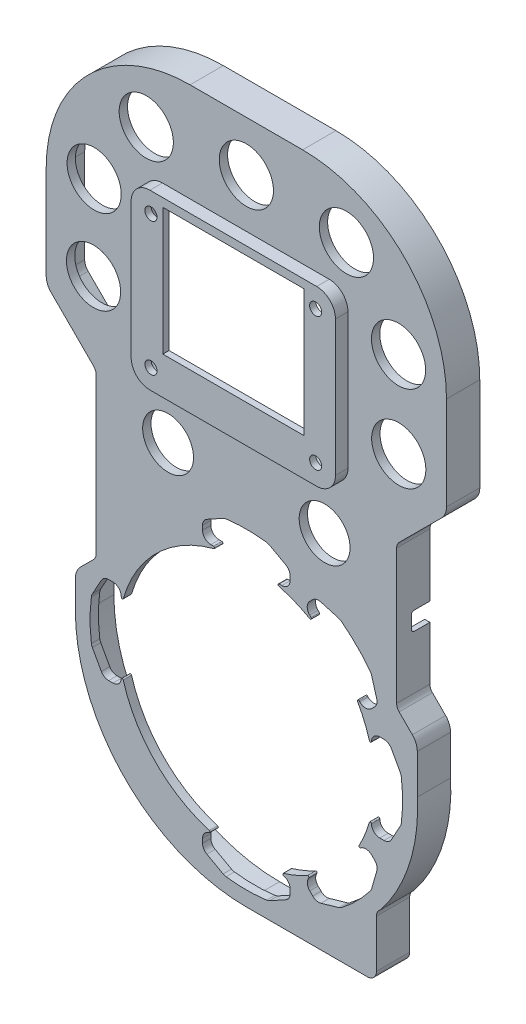
SolidWorks part; units mm, degrees
ref_plane "Front Plane" through (0, 0, 0) normal (0, 0, 1) x (1, 0, 0)
ref_plane "Top Plane" through (0, 0, 0) normal (0, 1, 0) x (1, 0, 0)
ref_plane "Right Plane" through (0, 0, 0) normal (1, 0, 0) x (0, 0, -1)
sketch "Sketch1" plane through (0, 0, 0) normal (0, 0, 1) x (1, 0, 0)
  line L36 (8.4982, -30) -> (7.3207, -30)
  line L37 (-7.3216, -30) -> (-8.502, -30)
  line L38 (-10.502, -32) -> (-10.502, -33.0199)
  line L39 (-9.469, -34.7705) -> (-5.5638, -36.9277)
  line L40 (5.5641, -36.9255) -> (9.4653, -34.7705)
  line L41 (10.4982, -33.0199) -> (10.4982, -32)
  line L42 (27.2278, -15.1986) -> (26.1368, -16.2896)
  line L43 (16.1034, -26.323) -> (15.2069, -27.2195)
  line L44 (15.2069, -30.0479) -> (15.928, -30.7691)
  line L45 (17.8964, -31.2766) -> (22.1831, -30.0405)
  line L46 (30.0502, -22.1703) -> (31.2849, -17.888)
  line L47 (30.7774, -15.9197) -> (30.0563, -15.1986)
  line L48 (29.9995, 8.3209) -> (29.9995, 6.3328)
  line L49 (29.9995, -6.7043) -> (29.9995, -8.6793)
  line L50 (31.9995, -10.6793) -> (33.0194, -10.6793)
  line L51 (34.77, -9.6463) -> (36.9272, -5.7411)
  line L52 (36.925, 5.3868) -> (34.77, 9.2879)
  line L53 (33.0194, 10.3209) -> (31.9995, 10.3209)
  line L54 (15.1817, 27.2112) -> (17.0463, 25.3466)
  line L55 (25.5318, 16.8611) -> (27.2026, 15.1902)
  line L56 (30.0311, 15.1902) -> (30.7522, 15.9114)
  line L57 (31.2597, 17.8797) -> (30.0237, 22.1664)
  line L58 (22.1535, 30.0335) -> (17.8712, 31.2683)
  line L59 (15.9029, 30.7608) -> (15.1817, 30.0396)
  line L60 (-8.5066, 30) -> (-5.5963, 30)
  line L61 (5.5954, 30) -> (8.4935, 30)
  line L62 (10.4935, 32) -> (10.4935, 33.0198)
  line L63 (9.4606, 34.7705) -> (5.5554, 36.9277)
  line L64 (-5.5725, 36.9254) -> (-9.4737, 34.7705)
  line L65 (-10.5066, 33.0198) -> (-10.5066, 32)
  line L66 (-30, -8.5009) -> (-30, -6.7063)
  line L67 (-30, 6.3349) -> (-30, 8.4993)
  line L68 (-32, 10.4993) -> (-33.0198, 10.4993)
  line L69 (-34.7705, 9.4663) -> (-36.9277, 5.5612)
  line L70 (-36.9254, -5.5668) -> (-34.7705, -9.4679)
  line L71 (-33.0198, -10.5009) -> (-32, -10.5009)
  line L116 (-40.999, 6.7981) -> (-41, -0.001)
  line L117 (-36.6421, 12.8391) -> (-39.8078, 9.6734)
  line L118 (-36.037, 51.567) -> (-36.037, 14.3011)
  line L119 (-46.8091, 63.1949) -> (-36.6429, 53.0287)
  line L120 (-48, 88.5) -> (-48, 66.0704)
  line L121 (13.5, 123) -> (-13.5, 123)
  line L122 (48.009, 66.0794) -> (48, 88.5)
  line L123 (36.6524, 53.0382) -> (46.8185, 63.2043)
  line L124 (36.037, 19.3) -> (36.037, 51.5702)
  line L125 (39.8081, 14.6731) -> (36.6429, 17.8383)
  line L126 (40.999, 2.3098) -> (40.999, 11.7976)
  line L127 (31.8051, -25.8491) -> (32.2996, -25.3546)
  line L128 (31.2, -38.795) -> (31.2, -27.3096)
  line L129 (0, -41.001) -> (28.999, -41.001)
  circle A1 centre (-18.768, 46) radius 6.1
  circle A4 centre (18.768, 46) radius 6.1
  arc A45 (17.0463, 25.3466) -> (5.5954, 30) centre (-0.0005, -0.1857) ccw
  arc A77 (-8.502, -30) -> (-10.502, -32) centre (-8.502, -32) ccw
  arc A78 (-10.502, -33.0199) -> (-9.469, -34.7705) centre (-8.502, -33.0199) ccw
  arc A79 (-5.5638, -36.9277) -> (-4.8555, -37.1602) centre (-4.5968, -35.177) ccw
  arc A80 (-4.8555, -37.1602) -> (4.8567, -37.1579) centre (-0.0084, 0) ccw
  arc A81 (4.8567, -37.1579) -> (5.5641, -36.9255) centre (4.5971, -35.1748) ccw
  arc A82 (9.4653, -34.7705) -> (10.4982, -33.0199) centre (8.4982, -33.0199) ccw
  arc A83 (10.4982, -32) -> (8.4982, -30) centre (8.4982, -32) ccw
  arc A88 (15.2069, -27.2195) -> (15.2069, -30.0479) centre (16.6211, -28.6337) ccw
  arc A89 (15.928, -30.7691) -> (17.8964, -31.2766) centre (17.3423, -29.3549) ccw
  arc A90 (22.1831, -30.0405) -> (22.8484, -29.7041) centre (21.629, -28.1188) ccw
  arc A91 (22.8484, -29.7041) -> (29.7143, -22.8348) centre (-0.0004, -0.0005) ccw
  arc A92 (29.7143, -22.8348) -> (30.0502, -22.1703) centre (28.1285, -21.6162) ccw
  arc A93 (31.2849, -17.888) -> (30.7774, -15.9197) centre (29.3632, -17.3339) ccw
  arc A94 (30.0563, -15.1986) -> (27.2278, -15.1986) centre (28.642, -16.6128) ccw
  arc A99 (29.9995, -8.6793) -> (31.9995, -10.6793) centre (31.9995, -8.6793) ccw
  arc A100 (33.0194, -10.6793) -> (34.77, -9.6463) centre (33.0194, -8.6793) ccw
  arc A101 (36.9272, -5.7411) -> (37.1598, -5.0328) centre (35.1766, -4.7741) ccw
  arc A102 (37.1598, -5.0328) -> (37.1574, 4.6794) centre (-0.0005, -0.1857) ccw
  arc A103 (37.1574, 4.6794) -> (36.925, 5.3868) centre (35.1743, 4.4198) ccw
  arc A104 (34.77, 9.2879) -> (33.0194, 10.3209) centre (33.0194, 8.3209) ccw
  arc A105 (31.9995, 10.3209) -> (29.9995, 8.3209) centre (31.9995, 8.3209) ccw
  arc A110 (27.2026, 15.1902) -> (30.0311, 15.1902) centre (28.6169, 16.6045) ccw
  arc A111 (30.7522, 15.9114) -> (31.2597, 17.8797) centre (29.338, 17.3256) ccw
  arc A112 (30.0237, 22.1664) -> (29.6872, 22.8318) centre (28.102, 21.6123) ccw
  arc A113 (29.6872, 22.8318) -> (22.818, 29.6976) centre (-0.0164, -0.0171) ccw
  arc A114 (22.818, 29.6976) -> (22.1535, 30.0335) centre (21.5994, 28.1118) ccw
  arc A115 (17.8712, 31.2683) -> (15.9029, 30.7608) centre (17.3171, 29.3465) ccw
  arc A116 (15.1817, 30.0396) -> (15.1817, 27.2112) centre (16.5959, 28.6254) ccw
  arc A121 (8.4935, 30) -> (10.4935, 32) centre (8.4935, 32) ccw
  arc A122 (10.4935, 33.0198) -> (9.4606, 34.7705) centre (8.4935, 33.0198) ccw
  arc A123 (5.5554, 36.9277) -> (4.8471, 37.1602) centre (4.5884, 35.177) ccw
  arc A124 (4.8471, 37.1602) -> (-4.8651, 37.1579) centre (0, 0) ccw
  arc A125 (-4.8651, 37.1579) -> (-5.5725, 36.9254) centre (-4.6055, 35.1748) ccw
  arc A126 (-9.4737, 34.7705) -> (-10.5066, 33.0198) centre (-8.5066, 33.0198) ccw
  arc A127 (-10.5066, 32) -> (-8.5066, 30) centre (-8.5066, 32) ccw
  arc A132 (-30, 8.4993) -> (-32, 10.4993) centre (-32, 8.4993) ccw
  arc A133 (-33.0198, 10.4993) -> (-34.7705, 9.4663) centre (-33.0198, 8.4993) ccw
  arc A134 (-36.9277, 5.5612) -> (-37.1602, 4.8528) centre (-35.177, 4.5941) ccw
  arc A135 (-37.1602, 4.8528) -> (-37.1579, -4.8594) centre (0, 0.0057) ccw
  arc A136 (-37.1579, -4.8594) -> (-36.9254, -5.5668) centre (-35.1748, -4.5997) ccw
  arc A137 (-34.7705, -9.4679) -> (-33.0198, -10.5009) centre (-33.0198, -8.5009) ccw
  arc A138 (-32, -10.5009) -> (-30, -8.5009) centre (-32, -8.5009) ccw
  circle A139 centre (36.55, 71.3501) radius 6.5
  circle A140 centre (36.5, 92.0001) radius 6.5
  circle A141 centre (23.9999, 109.0001) radius 6.5
  circle A142 centre (0.0001, 111) radius 6.5
  circle A143 centre (-24.0001, 108.9999) radius 6.5
  circle A144 centre (-36.5, 91.9999) radius 6.5
  circle A145 centre (-36.65, 71.6499) radius 6.5
  arc A146 (29.9995, 6.3328) -> (25.5318, 16.8611) centre (-0.0005, -0.1857) ccw
  arc A147 (26.1368, -16.2896) -> (29.9995, -6.7043) centre (-0.0005, -0.1857) ccw
  arc A148 (7.3207, -30) -> (16.1034, -26.323) centre (-0.0005, -0.1857) ccw
  arc A149 (-30, -6.7063) -> (-7.3216, -30) centre (-0.0005, -0.1857) ccw
  arc A160 (-5.5963, 30) -> (-30, 6.3349) centre (-0.0005, -0.1857) ccw
  arc A188 (-41, -0.001) -> (0, -41.001) centre (0.0009, -0.0001) ccw
  arc A189 (-39.8078, 9.6734) -> (-40.999, 6.7981) centre (-36.9358, 6.7992) ccw
  arc A190 (-36.6421, 12.8391) -> (-36.037, 14.3011) centre (-38.1114, 14.3035) ccw
  arc A191 (-36.037, 51.567) -> (-36.6429, 53.0287) centre (-38.1114, 51.5635) ccw
  arc A192 (-48, 66.0704) -> (-46.8091, 63.1949) centre (-43.9368, 66.0688) ccw
  arc A193 (-13.5, 123) -> (-48, 88.5) centre (-13.4997, 88.4997) ccw
  arc A194 (48, 88.5) -> (13.5, 123) centre (13.4997, 88.4997) ccw
  arc A195 (46.8185, 63.2043) -> (48.009, 66.0794) centre (43.9392, 66.0805) ccw
  arc A196 (36.6524, 53.0382) -> (36.037, 51.5702) centre (38.1602, 51.5431) ccw
  arc A197 (36.037, 19.3) -> (36.6429, 17.8383) centre (38.1114, 19.3035) ccw
  arc A198 (40.999, 11.7976) -> (39.8081, 14.6731) centre (36.9358, 11.7992) ccw
  arc A199 (32.2996, -25.3546) -> (40.999, 2.3098) centre (0.058, -0.0158) ccw
  arc A200 (31.8051, -25.8491) -> (31.2, -27.3096) centre (33.2632, -27.3088) ccw
  arc A201 (28.999, -41.001) -> (31.2, -38.795) centre (28.9913, -38.7924) ccw
extrude "Boss-Extrude1" add sketch "Sketch1" along normal blind 2
sketch "Sketch2" plane through (0, 0, 2) normal (0, 0, 1) x (1, 0, 0)
  line L21 (16.773, 59.804) -> (19.873, 59.804)
  line L22 (22.373, 62.304) -> (22.373, 94.804)
  line L23 (19.873, 97.304) -> (16.773, 97.304)
  line L24 (16.773, 97.304) -> (-17.027, 97.304)
  line L28 (-17.027, 59.804) -> (16.773, 59.804)
  line L32 (-22.627, 94.804) -> (-22.627, 62.304)
  line L33 (-20.127, 59.804) -> (-17.027, 59.804)
  line L35 (-17.027, 97.304) -> (-20.127, 97.304)
  line L37 (-17.027, 97.304) -> (16.773, 97.304)
  spline S6 degree 3 poles (19.873, 59.804) (21.3375, 59.804) (22.373, 60.8395) (22.373, 62.304) knots 0 0 0 0 1 1 1 1 weights 1 0.804738 0.804738 1
  spline S7 degree 3 poles (22.373, 94.804) (22.373, 96.2685) (21.3375, 97.304) (19.873, 97.304) knots 0 0 0 0 1 1 1 1 weights 1 0.804738 0.804738 1
  spline S8 degree 3 poles (-20.127, 97.304) (-21.5915, 97.304) (-22.627, 96.2685) (-22.627, 94.804) knots 0 0 0 0 1 1 1 1 weights 1 0.804738 0.804738 1
  spline S9 degree 3 poles (-22.627, 62.304) (-22.627, 60.8395) (-21.5915, 59.804) (-20.127, 59.804) knots 0 0 0 0 1 1 1 1 weights 1 0.804738 0.804738 1
sketch "Sketch3" plane through (0, 0, 2) normal (0, 0, 1) x (1, 0, 0)
  line L64 (-17.027, 99.304) -> (-20.127, 99.304)
  line L65 (-24.627, 94.804) -> (-24.627, 62.304)
  line L66 (-20.127, 57.804) -> (-17.027, 57.804)
  line L67 (-17.027, 57.804) -> (16.773, 57.804)
  line L68 (16.773, 57.804) -> (19.873, 57.804)
  line L69 (24.373, 62.304) -> (24.373, 94.804)
  line L70 (19.873, 99.304) -> (16.773, 99.304)
  line L71 (16.773, 99.304) -> (-17.027, 99.304)
  line L72 (-17.027, 99.304) -> (-20.127, 99.304)
  line L73 (-24.627, 94.804) -> (-24.627, 62.304)
  line L74 (-20.127, 57.804) -> (-17.027, 57.804)
  line L75 (-17.027, 57.804) -> (16.773, 57.804)
  line L76 (16.773, 57.804) -> (19.873, 57.804)
  line L77 (24.373, 62.304) -> (24.373, 94.804)
  line L78 (19.873, 99.304) -> (16.773, 99.304)
  line L79 (16.773, 99.304) -> (-17.027, 99.304)
  arc A29 (-20.127, 99.304) -> (-24.627, 94.804) centre (-20.127, 94.804) ccw
  arc A30 (-24.627, 62.304) -> (-20.127, 57.804) centre (-20.127, 62.304) ccw
  arc A31 (19.873, 57.804) -> (24.373, 62.304) centre (19.873, 62.304) ccw
  arc A32 (24.373, 94.804) -> (19.873, 99.304) centre (19.873, 94.804) ccw
  arc A33 (-20.127, 99.304) -> (-24.627, 94.804) centre (-20.127, 94.804) ccw
  arc A34 (-24.627, 62.304) -> (-20.127, 57.804) centre (-20.127, 62.304) ccw
  arc A35 (19.873, 57.804) -> (24.373, 62.304) centre (19.873, 62.304) ccw
  arc A36 (24.373, 94.804) -> (19.873, 99.304) centre (19.873, 94.804) ccw
  dimension "D1" = 2
extrude "Boss-Extrude2" add sketch "Sketch3" along normal blind 3
sketch "Sketch4" plane through (0, 0, 5) normal (0, 0, 1) x (1, 0, 0)
  line L4 (-17.027, 66.804) -> (16.773, 66.804)
  line L5 (16.773, 66.804) -> (16.773, 97.304)
  line L6 (-17.027, 97.304) -> (-17.027, 66.804)
  line L7 (-17.027, 97.304) -> (16.773, 97.304)
extrude "Cut-Extrude1" cut sketch "Sketch4" against normal through all
sketch "Sketch5" plane through (0, 0, 0) normal (0, 0, 1) x (1, 0, 0)
  line L58 (-22.877, 94.804) -> (-22.877, 62.304)
  line L59 (-20.127, 59.554) -> (-17.027, 59.554)
  line L60 (-17.027, 59.554) -> (16.773, 59.554)
  line L61 (16.773, 59.554) -> (19.873, 59.554)
  line L62 (22.623, 62.304) -> (22.623, 94.804)
  line L63 (19.873, 97.554) -> (16.773, 97.554)
  line L64 (16.773, 97.554) -> (-17.027, 97.554)
  line L65 (-17.027, 97.554) -> (-20.127, 97.554)
  line L66 (-22.877, 94.804) -> (-22.877, 62.304)
  line L67 (-20.127, 59.554) -> (-17.027, 59.554)
  line L68 (-17.027, 59.554) -> (16.773, 59.554)
  line L69 (16.773, 59.554) -> (19.873, 59.554)
  line L70 (22.623, 62.304) -> (22.623, 94.804)
  line L71 (19.873, 97.554) -> (16.773, 97.554)
  line L72 (16.773, 97.554) -> (-17.027, 97.554)
  line L73 (-17.027, 97.554) -> (-20.127, 97.554)
  arc A31 (-22.877, 62.304) -> (-20.127, 59.554) centre (-20.127, 62.304) ccw
  arc A32 (19.873, 59.554) -> (22.623, 62.304) centre (19.873, 62.304) ccw
  arc A33 (22.623, 94.804) -> (19.873, 97.554) centre (19.873, 94.804) ccw
  arc A34 (-20.127, 97.554) -> (-22.877, 94.804) centre (-20.127, 94.804) ccw
  arc A35 (-22.877, 62.304) -> (-20.127, 59.554) centre (-20.127, 62.304) ccw
  arc A36 (19.873, 59.554) -> (22.623, 62.304) centre (19.873, 62.304) ccw
  arc A37 (22.623, 94.804) -> (19.873, 97.554) centre (19.873, 94.804) ccw
  arc A38 (-20.127, 97.554) -> (-22.877, 94.804) centre (-20.127, 94.804) ccw
  dimension "D1" = 0.25
extrude "Cut-Extrude2" cut sketch "Sketch5" along normal offset from surface (3.5 mm away) 1.5 up to face at (-0.127, 82.054, 5)
sketch "Sketch8" plane through (0, 0, 3.5) normal (0, 0, -1) x (-1, 0, 0)
  line L0 (21.327, 94.529) -> (18.427, 94.529)
  line L1 (-18.173, 94.529) -> (-21.073, 94.529)
  line L2 (21.327, 62.579) -> (18.427, 62.579)
  line L3 (-18.173, 62.579) -> (-21.073, 62.579)
  spline S4 degree 3 poles (21.327, 94.529) (21.327, 97.429) (18.427, 97.429) (18.427, 94.529) (18.427, 91.629) (21.327, 91.629) (21.327, 94.529) (21.327, 97.429) (18.427, 97.429) knots -0.5 0 0 0 0.5 0.5 0.5 1 1 1 1.5 1.5 1.5 weights 1 0.333333 0.333333 1 0.333333 0.333333 1 0.333333 0.333333 only from (21.327, 94.529) to (21.327, 94.529)
  spline S5 degree 3 poles (21.327, 62.579) (21.327, 65.479) (18.427, 65.479) (18.427, 62.579) (18.427, 59.679) (21.327, 59.679) (21.327, 62.579) (21.327, 65.479) (18.427, 65.479) knots -0.5 0 0 0 0.5 0.5 0.5 1 1 1 1.5 1.5 1.5 weights 1 0.333333 0.333333 1 0.333333 0.333333 1 0.333333 0.333333 only from (21.327, 62.579) to (21.327, 62.579)
  spline S6 degree 3 poles (-18.173, 62.579) (-18.173, 65.479) (-21.073, 65.479) (-21.073, 62.579) (-21.073, 59.679) (-18.173, 59.679) (-18.173, 62.579) (-18.173, 65.479) (-21.073, 65.479) knots -0.5 0 0 0 0.5 0.5 0.5 1 1 1 1.5 1.5 1.5 weights 1 0.333333 0.333333 1 0.333333 0.333333 1 0.333333 0.333333 only from (-18.173, 62.579) to (-18.173, 62.579)
  spline S7 degree 3 poles (-18.173, 94.529) (-18.173, 97.429) (-21.073, 97.429) (-21.073, 94.529) (-21.073, 91.629) (-18.173, 91.629) (-18.173, 94.529) (-18.173, 97.429) (-21.073, 97.429) knots -0.5 0 0 0 0.5 0.5 0.5 1 1 1 1.5 1.5 1.5 weights 1 0.333333 0.333333 1 0.333333 0.333333 1 0.333333 0.333333 only from (-18.173, 94.529) to (-18.173, 94.529)
sketch "Sketch11" plane through (0, 0, 5) normal (0, 0, 1) x (1, 0, 0)
  circle A0 centre (19.623, 94.529) radius 1
  circle A1 centre (-19.877, 94.529) radius 1
  circle A2 centre (19.623, 62.579) radius 1
  circle A3 centre (-19.877, 62.579) radius 1
extrude "Cut-Extrude5" cut sketch "Sketch8" against normal through all contours S4 | S7 | S6 | S5
sketch "Sketch9" plane through (0, 0, 0) normal (0, 0, -1) x (-1, 0, 0)
  line L0 (-46.75, 88.4998) -> (-46.759, 66.0793)
  line L1 (-45.9344, 64.0879) -> (-35.7669, 53.9205)
  line L2 (-34.787, 51.5773) -> (-34.787, 19.299)
  line L3 (-35.7585, 16.9549) -> (-38.9243, 13.7891)
  line L4 (-39.749, 11.7979) -> (-39.749, 2.2741)
  line L5 (-31.3625, -24.5239) -> (-30.9215, -24.965)
  line L6 (-29.95, -27.3099) -> (-29.95, -38.7943)
  line L7 (-28.9964, -39.751) -> (0, -39.751)
  line L8 (39.75, -0.0011) -> (39.749, 6.7982)
  line L9 (38.9241, 8.7893) -> (35.7575, 11.956)
  line L10 (34.787, 14.3004) -> (34.787, 51.568)
  line L11 (35.7585, 53.9121) -> (45.9253, 64.0789)
  line L12 (46.75, 66.0701) -> (46.75, 88.5)
  line L13 (13.5, 121.75) -> (-13.5, 121.75)
  line L14 (41, -0.001) -> (40.999, 6.7981)
  line L15 (39.8078, 9.6734) -> (36.6421, 12.8391)
  line L16 (36.037, 14.3011) -> (36.037, 51.567)
  line L17 (36.6429, 53.0287) -> (46.8091, 63.1949)
  line L18 (48, 66.0704) -> (48, 88.5)
  line L19 (13.5, 123) -> (-13.5, 123)
  line L20 (-48, 88.5) -> (-48.009, 66.0794)
  line L21 (-46.8185, 63.2043) -> (-36.6524, 53.0382)
  line L22 (-36.037, 51.5702) -> (-36.037, 19.3)
  line L23 (-36.6429, 17.8383) -> (-39.8081, 14.6731)
  line L24 (-40.999, 11.7976) -> (-40.999, 2.3098)
  line L25 (-32.2996, -25.3546) -> (-31.8051, -25.8491)
  line L26 (-31.2, -27.3096) -> (-31.2, -38.795)
  line L27 (-28.999, -41.001) -> (0, -41.001)
  line L28 (41, -0.001) -> (40.999, 6.7981)
  line L29 (39.8078, 9.6734) -> (36.6421, 12.8391)
  line L30 (36.037, 14.3011) -> (36.037, 51.567)
  line L31 (36.6429, 53.0287) -> (46.8091, 63.1949)
  line L32 (48, 66.0704) -> (48, 88.5)
  line L33 (13.5, 123) -> (-13.5, 123)
  line L34 (-48, 88.5) -> (-48.009, 66.0794)
  line L35 (-46.8185, 63.2043) -> (-36.6524, 53.0382)
  line L36 (-36.037, 51.5702) -> (-36.037, 19.3)
  line L37 (-36.6429, 17.8383) -> (-39.8081, 14.6731)
  line L38 (-40.999, 11.7976) -> (-40.999, 2.3098)
  line L39 (-32.2996, -25.3546) -> (-31.8051, -25.8491)
  line L40 (-31.2, -27.3096) -> (-31.2, -38.795)
  line L41 (-28.999, -41.001) -> (0, -41.001)
  arc A0 (-13.5, 121.75) -> (-46.75, 88.4998) centre (-13.4997, 88.4997) ccw
  arc A1 (-46.759, 66.0793) -> (-45.9344, 64.0879) centre (-43.9392, 66.0805) ccw
  arc A2 (-34.787, 51.5773) -> (-35.7669, 53.9205) centre (-38.1602, 51.5431) ccw
  arc A3 (-35.7585, 16.9549) -> (-34.787, 19.299) centre (-38.1114, 19.3035) ccw
  arc A4 (-38.9243, 13.7891) -> (-39.749, 11.7979) centre (-36.9358, 11.7992) ccw
  arc A5 (-39.749, 2.2741) -> (-31.3625, -24.5239) centre (-0.058, -0.0158) ccw
  arc A6 (-29.95, -27.3099) -> (-30.9215, -24.965) centre (-33.2632, -27.3088) ccw
  arc A7 (-29.95, -38.7943) -> (-28.9964, -39.751) centre (-28.9913, -38.7924) ccw
  arc A8 (0, -39.751) -> (39.75, -0.0011) centre (-0.0009, -0.0001) ccw
  arc A9 (39.749, 6.7982) -> (38.9241, 8.7893) centre (36.9358, 6.7992) ccw
  arc A10 (34.787, 14.3004) -> (35.7575, 11.956) centre (38.1114, 14.3035) ccw
  arc A11 (35.7585, 53.9121) -> (34.787, 51.568) centre (38.1114, 51.5635) ccw
  arc A12 (45.9253, 64.0789) -> (46.75, 66.0701) centre (43.9368, 66.0688) ccw
  arc A13 (46.75, 88.5) -> (13.5, 121.75) centre (13.4997, 88.4997) ccw
  arc A14 (0, -41.001) -> (41, -0.001) centre (-0.0009, -0.0001) ccw
  arc A15 (40.999, 6.7981) -> (39.8078, 9.6734) centre (36.9358, 6.7992) ccw
  arc A16 (36.037, 14.3011) -> (36.6421, 12.8391) centre (38.1114, 14.3035) ccw
  arc A17 (36.6429, 53.0287) -> (36.037, 51.567) centre (38.1114, 51.5635) ccw
  arc A18 (46.8091, 63.1949) -> (48, 66.0704) centre (43.9368, 66.0688) ccw
  arc A19 (48, 88.5) -> (13.5, 123) centre (13.4997, 88.4997) ccw
  arc A20 (-13.5, 123) -> (-48, 88.5) centre (-13.4997, 88.4997) ccw
  arc A21 (-48.009, 66.0794) -> (-46.8185, 63.2043) centre (-43.9392, 66.0805) ccw
  arc A22 (-36.037, 51.5702) -> (-36.6524, 53.0382) centre (-38.1602, 51.5431) ccw
  arc A23 (-36.6429, 17.8383) -> (-36.037, 19.3) centre (-38.1114, 19.3035) ccw
  arc A24 (-39.8081, 14.6731) -> (-40.999, 11.7976) centre (-36.9358, 11.7992) ccw
  arc A25 (-40.999, 2.3098) -> (-32.2996, -25.3546) centre (-0.058, -0.0158) ccw
  arc A26 (-31.2, -27.3096) -> (-31.8051, -25.8491) centre (-33.2632, -27.3088) ccw
  arc A27 (-31.2, -38.795) -> (-28.999, -41.001) centre (-28.9913, -38.7924) ccw
  arc A28 (0, -41.001) -> (41, -0.001) centre (-0.0009, -0.0001) ccw
  arc A29 (40.999, 6.7981) -> (39.8078, 9.6734) centre (36.9358, 6.7992) ccw
  arc A30 (36.037, 14.3011) -> (36.6421, 12.8391) centre (38.1114, 14.3035) ccw
  arc A31 (36.6429, 53.0287) -> (36.037, 51.567) centre (38.1114, 51.5635) ccw
  arc A32 (46.8091, 63.1949) -> (48, 66.0704) centre (43.9368, 66.0688) ccw
  arc A33 (48, 88.5) -> (13.5, 123) centre (13.4997, 88.4997) ccw
  arc A34 (-13.5, 123) -> (-48, 88.5) centre (-13.4997, 88.4997) ccw
  arc A35 (-48.009, 66.0794) -> (-46.8185, 63.2043) centre (-43.9392, 66.0805) ccw
  arc A36 (-36.037, 51.5702) -> (-36.6524, 53.0382) centre (-38.1602, 51.5431) ccw
  arc A37 (-36.6429, 17.8383) -> (-36.037, 19.3) centre (-38.1114, 19.3035) ccw
  arc A38 (-39.8081, 14.6731) -> (-40.999, 11.7976) centre (-36.9358, 11.7992) ccw
  arc A39 (-40.999, 2.3098) -> (-32.2996, -25.3546) centre (-0.058, -0.0158) ccw
  arc A40 (-31.2, -27.3096) -> (-31.8051, -25.8491) centre (-33.2632, -27.3088) ccw
  arc A41 (-31.2, -38.795) -> (-28.999, -41.001) centre (-28.9913, -38.7924) ccw
  dimension "D1" = 0
  dimension "D2" = 1.25
extrude "Boss-Extrude4" add sketch "Sketch9" along normal offset from surface (5.98 mm away) 0.25
sketch "Sketch10" plane through (-36.037, 0, 0) normal (-1, 0, 0) x (0, 0, 1)
  line L10 (-5.23, 36.55) -> (-2.23, 36.55)
  line L11 (-5.23, 36.55) -> (-2.23, 36.55)
  line L13 (-5.23, 32.15) -> (-2.23, 32.15)
  line L14 (-5.23, 32.15) -> (-2.23, 32.15)
  line L18 (-5.23, 36.55) -> (-5.98, 36.55)
  line L19 (-1.53, 32.85) -> (-1.53, 35.85)
  line L20 (-1.53, 32.85) -> (-1.53, 35.85)
  line L21 (-5.98, 14.3011) -> (-5.98, 51.567) construction
  line L22 (-5.98, 36.55) -> (-5.98, 32.15)
  line L23 (-5.98, 32.15) -> (-5.23, 32.15)
  arc A16 (-1.735, 36.345) -> (-2.23, 36.55) centre (-2.23, 35.85) ccw
  arc A17 (-1.53, 35.85) -> (-1.735, 36.345) centre (-2.23, 35.85) ccw
  arc A18 (-2.23, 32.15) -> (-1.735, 32.355) centre (-2.23, 32.85) ccw
  arc A19 (-1.735, 32.355) -> (-1.53, 32.85) centre (-2.23, 32.85) ccw
  arc A20 (-1.735, 36.345) -> (-2.23, 36.55) centre (-2.23, 35.85) ccw
  arc A21 (-1.53, 35.85) -> (-1.735, 36.345) centre (-2.23, 35.85) ccw
  arc A22 (-2.23, 32.15) -> (-1.735, 32.355) centre (-2.23, 32.85) ccw
  arc A23 (-1.735, 32.355) -> (-1.53, 32.85) centre (-2.23, 32.85) ccw
  dimension "D1" = 0.2
  dimension "D2" = 0.2
  dimension "D3" = 0.2
extrude "Cut-Extrude4" cut sketch "Sketch10" against normal through all
fillet "Fillet1" radius 0.25 12 edges at (5.5954, 30, 1) (-5.5963, 30, 1) (-30, 6.3349, 1) (-30, -6.7063, 1) (-7.3216, -30, 1) (7.3207, -30, 1) (16.1034, -26.323, 1) (26.1368, -16.2896, 1) (29.9995, -6.7043, 1) (29.9995, 6.3328, 1) (25.5318, 16.8611, 1) (17.0463, 25.3466, 1)
